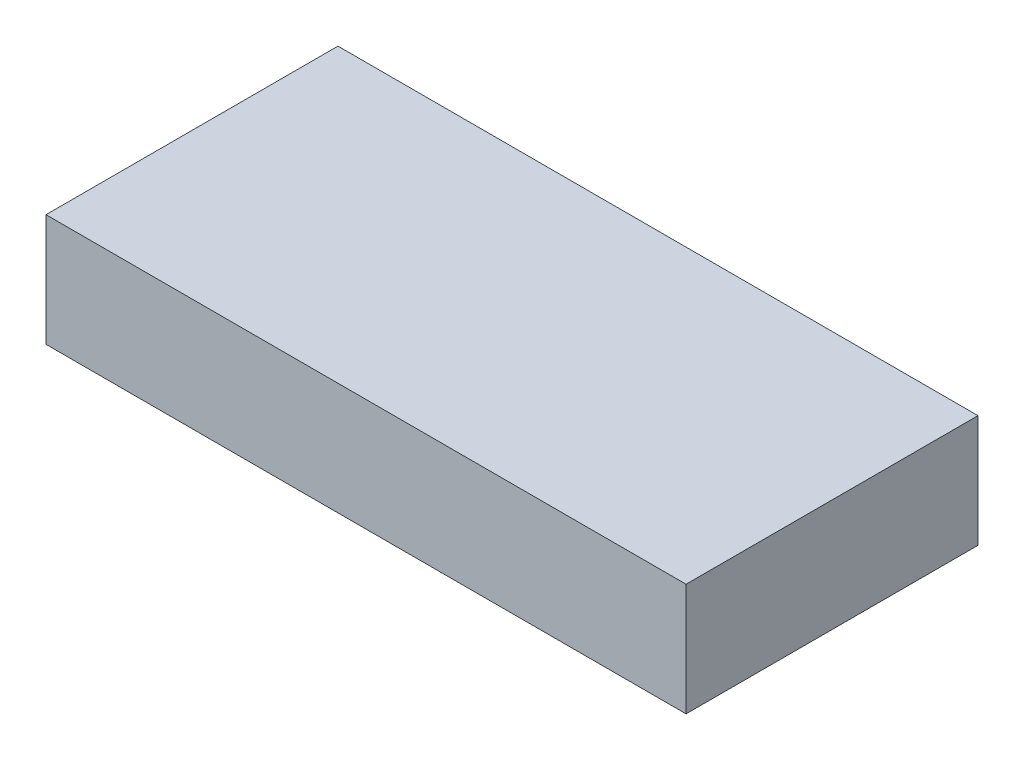
SolidWorks part; units mm, degrees
ref_plane "Front Plane" through (0, 0, 0) normal (0, 0, 1) x (1, 0, 0)
ref_plane "Top Plane" through (0, 0, 0) normal (0, 1, 0) x (1, 0, 0)
ref_plane "Right Plane" through (0, 0, 0) normal (1, 0, 0) x (0, 0, -1)
sketch "Sketch1" plane through (0, 0, 0) normal (0, 1, 0) x (1, 0, 0)
  line L0 (0, 0) -> (28.5, 0)
  line L1 (28.5, 0) -> (28.5, 13)
  line L2 (28.5, 13) -> (0, 13)
  line L3 (0, 0) -> (0, 13)
  dimension "D1" = 28.5
  dimension "D2" = 13
extrude "Boss-Extrude1" add sketch "Sketch1" along normal blind 5
